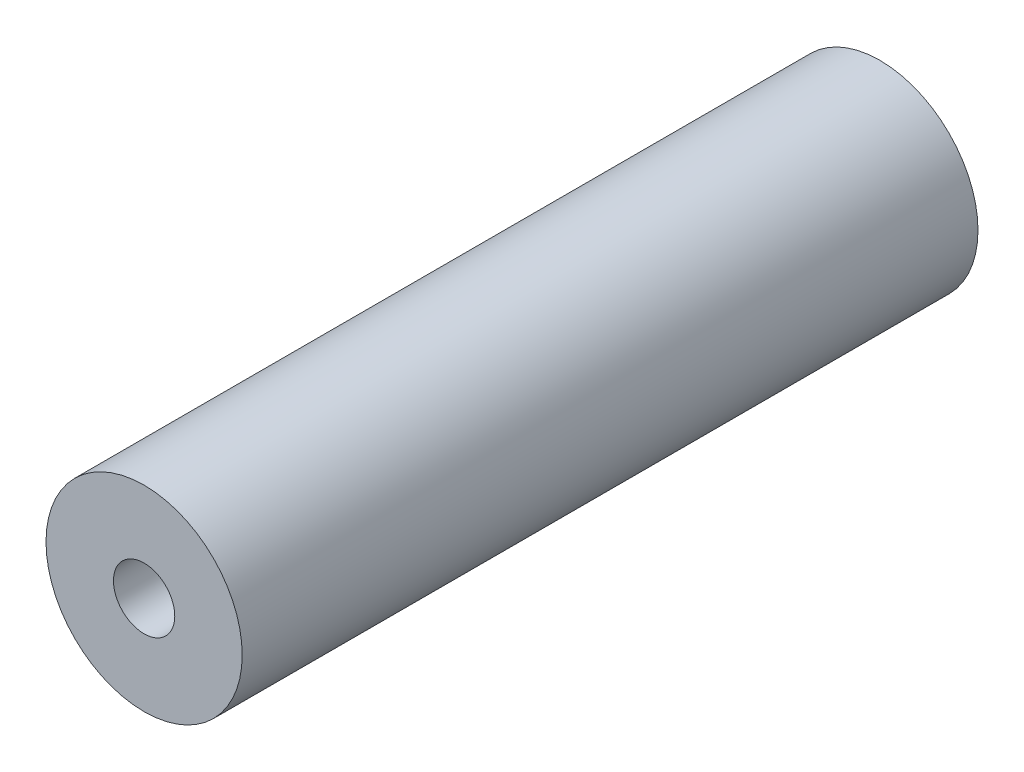
SolidWorks part; units mm, degrees
ref_plane "Front Plane" through (0, 0, 0) normal (0, 0, 1) x (1, 0, 0)
ref_plane "Top Plane" through (0, 0, 0) normal (0, 1, 0) x (1, 0, 0)
ref_plane "Right Plane" through (0, 0, 0) normal (1, 0, 0) x (0, 0, -1)
sketch "Sketch1" plane through (0, 0, 0) normal (0, 0, 1) x (1, 0, 0)
  circle A1 centre (0, 0) radius 4
  dimension "D1" = 8
extrude "Boss-Extrude1" add sketch "Sketch1" along normal mid plane 30
hole_wizard "M3 Tapped Hole1" positions "Sketch2" profile "Sketch3" tap size "M3" standard "ISO"
sketch "Sketch2" plane through (0, 0, 15) normal (0, 0, 1) x (1, 0, 0)
  point P0 (0, 0)
sketch "Sketch3" plane through (0, 0, 15) normal (1, 0, 0) x (0, -1, 0)
  line L0 (0, 0) -> (0, 8.2511)
  line L1 (0, 8.2511) -> (1.25, 7.5)
  line L2 (1.25, 7.5) -> (1.25, 0)
  line L5 (1.25, 0) -> (0, 0)
  line L10 (0, 8.2511) -> (-1.25, 7.5) construction
  line L11 (0, -6.35) -> (0, 107.95) construction
  dimension "Tap Drill Dia." = 2.5
  dimension "Tap Drill Depth" = 7.5
  dimension "Drill Angle" = 118
cosmetic thread "Hole Thread1"
mirror "Mirror1" about plane through (0, 0, 0) normal (0, 0, 1) of "M3 Tapped Hole1"
cosmetic thread "Hole Thread2" parameters "D1"=6, "D2"=3
